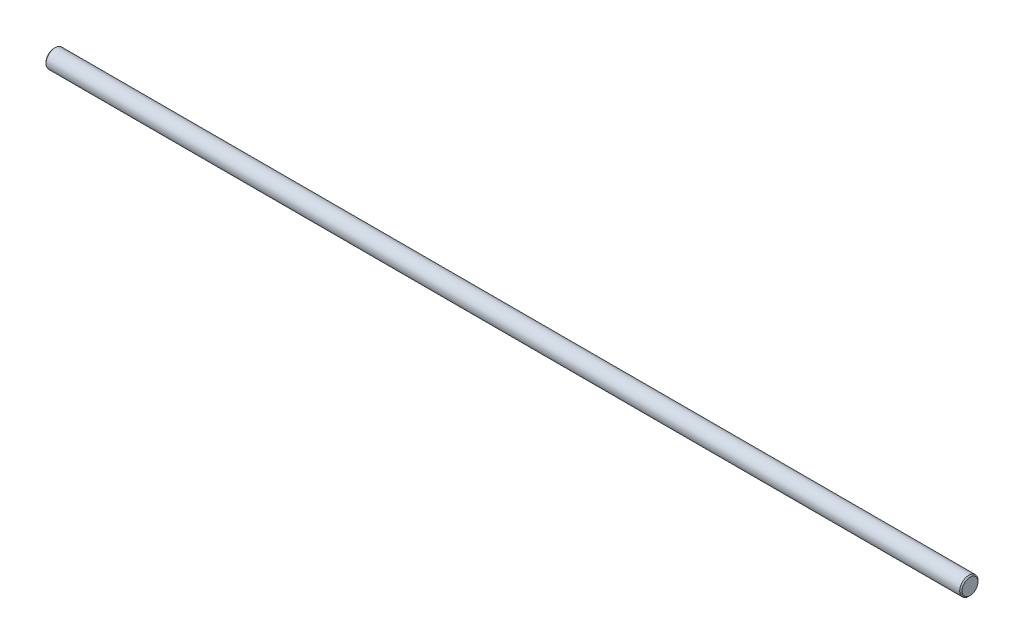
SolidWorks part; units mm, degrees
ref_plane "Front Plane" through (0, 0, 0) normal (0, 0, 1) x (1, 0, 0)
ref_plane "Top Plane" through (0, 0, 0) normal (0, 1, 0) x (1, 0, 0)
ref_plane "Right Plane" through (0, 0, 0) normal (1, 0, 0) x (0, 0, -1)
ref_plane "Plane1" through (0, 0, 0) normal (0, 0, 1) x (1, 0, 0)
sketch "Sketch1" plane through (0, 0, 0) normal (0, 0, 1) x (1, 0, 0)
  line L0 (0, 0) -> (0, 3.5)
  line L1 (0, 3.5) -> (0.5, 4)
  line L2 (0.5, 4) -> (399.5, 4)
  line L3 (399.5, 4) -> (400, 3.5)
  line L4 (400, 3.5) -> (400, 0)
  line L5 (400, 0) -> (0, 0)
  line L6 (400, 0) -> (0, 0) construction
revolve "Revolve1" add sketch "Sketch1" angle 360 about L6
